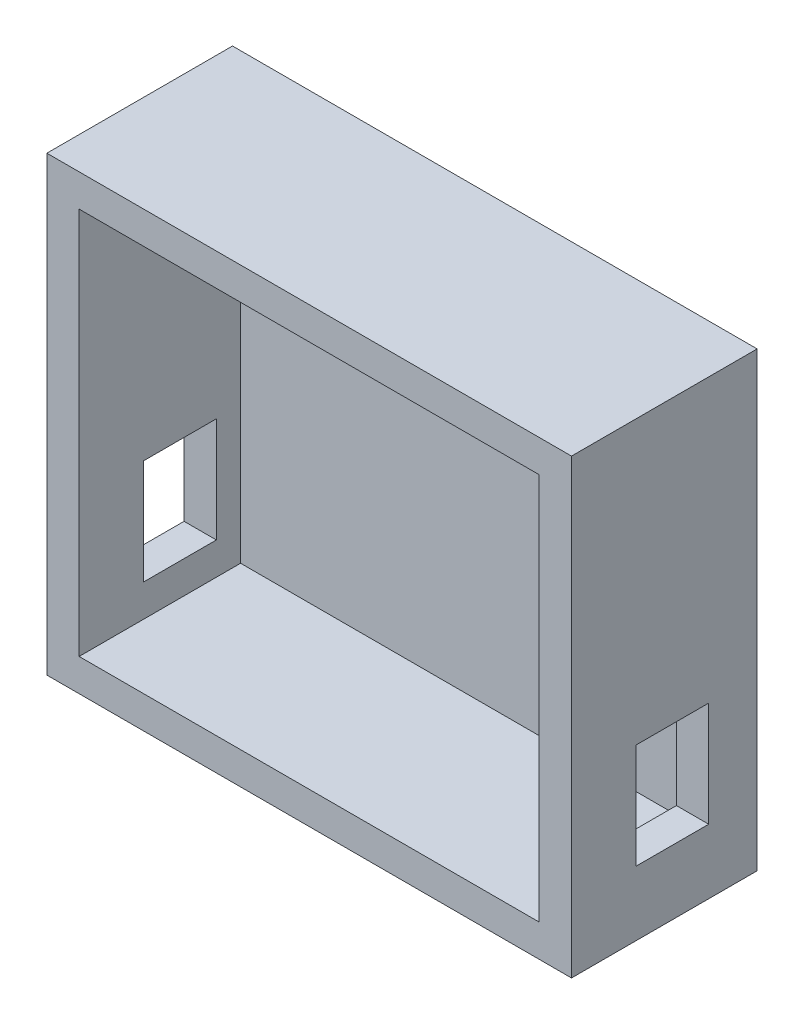
SolidWorks part; units mm, degrees
ref_plane "Front Plane" through (0, 0, 0) normal (0, 0, 1) x (1, 0, 0)
ref_plane "Top Plane" through (0, 0, 0) normal (0, 1, 0) x (1, 0, 0)
ref_plane "Right Plane" through (0, 0, 0) normal (1, 0, 0) x (0, 0, -1)
sketch "Sketch1" plane through (0, 0, 0) normal (0, 0, 1) x (1, 0, 0)
  line L1 (-32.5, 28) -> (32.5, 28)
  line L2 (-32.5, 28) -> (-32.5, -28)
  line L3 (-32.5, -28) -> (32.5, -28)
  line L4 (32.5, 28) -> (32.5, -28)
  line L5 (-32.5, 28) -> (32.5, -28) construction
  line L6 (-32.5, -28) -> (32.5, 28) construction
  point P0 (0, 0)
  dimension "D1" = 56
  dimension "D2" = 65
extrude "Boss-Extrude1" add sketch "Sketch1" along normal blind 23
sketch "Sketch2" plane through (0, 0, 23) normal (0, 0, 1) x (1, 0, 0)
  line L0 (32.5, 28) -> (-32.5, 28) construction
  line L1 (-28.5, 24) -> (28.5, 24)
  line L2 (-28.5, 24) -> (-28.5, -24)
  line L3 (-28.5, -24) -> (28.5, -24)
  line L4 (28.5, 24) -> (28.5, -24)
  line L5 (-28.5, 24) -> (28.5, -24) construction
  line L6 (-28.5, -24) -> (28.5, 24) construction
  point P0 (0, 0)
  point P8 (0, 0)
  dimension "D1" = 4
  dimension "D2" = 4
extrude "Cut-Extrude1" cut sketch "Sketch2" against normal blind 20
sketch "Sketch5" plane through (-32.5, 0, 0) normal (-1, 0, 0) x (0, 0, 1)
  line L0 (23, -28) -> (0, -28) construction
  line L1 (15, -7) -> (6, -7)
  line L2 (15, -7) -> (15, -20)
  line L3 (15, -20) -> (6, -20)
  line L4 (6, -7) -> (6, -20)
  line L5 (15, -7) -> (6, -20) construction
  line L6 (15, -20) -> (6, -7) construction
  point P0 (10.5, -13.5)
  dimension "D1" = 8
  dimension "D2" = 6
  dimension "D3" = 13
  dimension "D4" = 9
extrude "Cut-Extrude2" cut sketch "Sketch5" against normal through all
